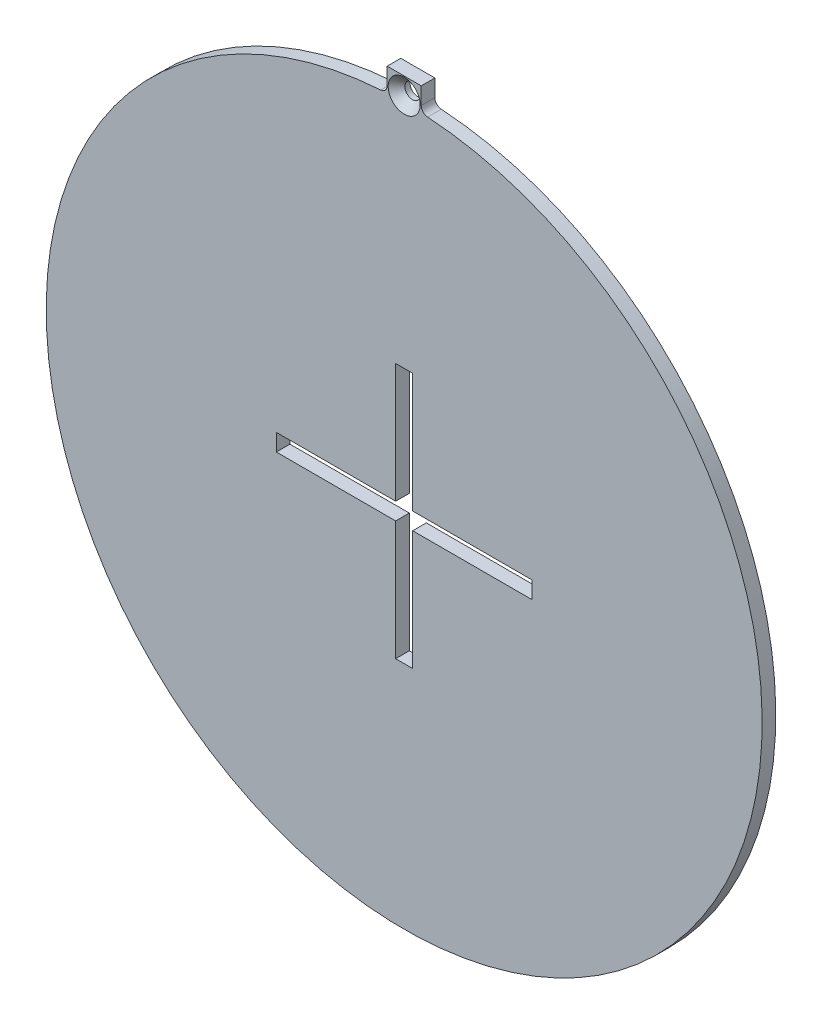
SolidWorks part; units mm, degrees
ref_plane "Front" through (0, 0, 0) normal (0, 0, 1) x (1, 0, 0)
ref_plane "Top" through (0, 0, 0) normal (0, 1, 0) x (1, 0, 0)
ref_plane "Right" through (0, 0, 0) normal (1, 0, 0) x (0, 0, -1)
sketch "Sketch1" plane through (0, 0, 0) normal (0, 0, 1) x (1, 0, 0)
  line L2 (5, 106.7708) -> (5, 111.7708)
  line L3 (5, 111.7708) -> (-5, 111.7708)
  line L4 (-5, 106.7708) -> (-5, 111.7708)
  arc A0 (-6.8692, 104.7751) -> (6.8692, 104.7751) centre (0, 0) ccw
  arc A1 (-6.8692, 104.7751) -> (-5, 106.7708) centre (-7, 106.7708) ccw
  arc A2 (6.8692, 104.7751) -> (5, 106.7708) centre (7, 106.7708) cw
  point P1 (0, 111.7708)
  dimension "D1" = 210
  dimension "D3" = 2
  dimension "D2" = 10
  dimension "D4" = 5
extrude "Boss-Extrude1" add sketch "Sketch1" along normal blind 4
sketch "Sketch2" plane through (0, 0, 0) normal (0, 0, -1) x (-1, 0, 0)
  line L0 (-2.5, -2.5) -> (-2.5, -37.5)
  line L1 (-2.5, 37.5) -> (2.5, 37.5)
  line L2 (-2.5, 37.5) -> (-2.5, 2.5)
  line L3 (-2.5, -37.5) -> (2.5, -37.5)
  line L4 (2.5, 37.5) -> (2.5, 2.5)
  line L5 (-37.5, 2.5) -> (-2.5, 2.5)
  line L6 (-37.5, 2.5) -> (-37.5, -2.5)
  line L7 (-37.5, -2.5) -> (-2.5, -2.5)
  line L8 (37.5, 2.5) -> (37.5, -2.5)
  line L9 (2.5, 2.5) -> (37.5, 2.5)
  line L10 (2.5, -2.5) -> (2.5, -37.5)
  line L11 (2.5, -2.5) -> (37.5, -2.5)
  line L12 (-2.5, -2.5) -> (2.5, 2.5) construction
  point P12 (0, 0)
  dimension "D1" = 5
  dimension "D2" = 35
extrude "Cut-Extrude1" cut sketch "Sketch2" against normal up to next
hole_wizard "CSK for M4 Countersunk Flat Head Screw1" positions "3DSketch1" profile "Sketch3" countersink size "M4" standard "ISO" end condition up to next
sketch3d "3DSketch1"
  line L3 (5, 111.7708, 4) -> (-5, 111.7708, 4) construction
  point P0 (0, 106.7708, 4)
  point P22 (0, 111.7708, 4)
  dimension "D1" = 5
sketch "Sketch3" plane through (0, 106.7708, 4) normal (1, 0, 0) x (0, -1, 0)
  line L0 (0, 0) -> (0, 4)
  line L1 (0, 4) -> (2.25, 4)
  line L2 (2.25, 4) -> (2.25, 2.45)
  line L3 (2.25, 2.45) -> (4.7, 0)
  line L5 (4.7, 0) -> (0, 0)
  line L6 (-2.25, 2.45) -> (-4.7, 0) construction
  line L11 (0, -6.35) -> (0, 107.95) construction
  dimension "Thru Hole Dia." = 4.5
  dimension "Thru Hole Depth" = 4
  dimension "Near C'Sink Dia." = 9.4
  dimension "Near C'Sink Angle" = 90
